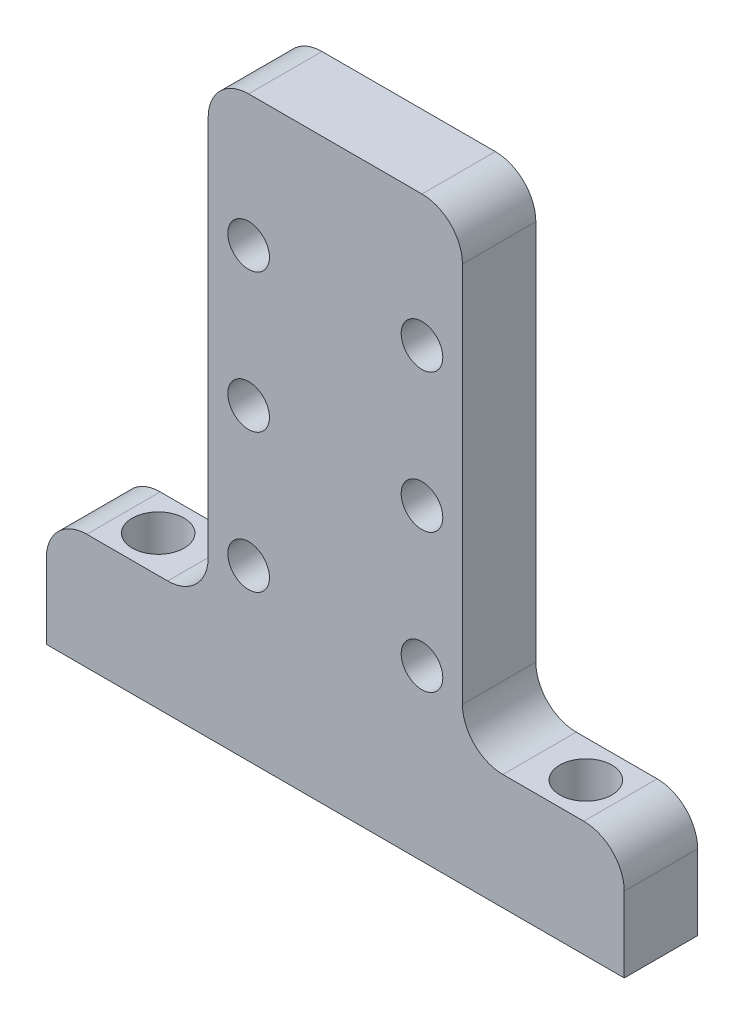
SolidWorks part; units mm, degrees
ref_plane "Front Plane" through (0, 0, 0) normal (0, 0, 1) x (1, 0, 0)
ref_plane "Top Plane" through (0, 0, 0) normal (0, 1, 0) x (1, 0, 0)
ref_plane "Right Plane" through (0, 0, 0) normal (1, 0, 0) x (0, 0, -1)
sketch "Sketch1" plane through (0, 0, 0) normal (0, 0, 1) x (1, 0, 0)
  line L0 (-25, 0) -> (25, 0)
  line L1 (25, 0) -> (25, 10)
  line L2 (25, 10) -> (11, 10)
  line L3 (11, 10) -> (11, 50)
  line L4 (11, 50) -> (-11, 50)
  line L5 (0, 50) -> (0, 0) construction
  line L6 (-25, 0) -> (-25, 10)
  line L7 (-25, 10) -> (-11, 10)
  line L8 (-11, 10) -> (-11, 50)
  dimension "D1" = 50
  dimension "D2" = 22
  dimension "D3" = 40
  dimension "D4" = 10
extrude "Boss-Extrude1" add sketch "Sketch1" along normal blind 6.35
sketch "Sketch4" plane through (0, 10, 0) normal (0, 1, 0) x (1, 0, 0)
  line L0 (-25, -3.175) -> (25, -3.175) construction
  line L1 (-25, -6.35) -> (-25, 0) construction
  line L2 (25, -6.35) -> (25, 0) construction
  line L3 (0, 0) -> (0, -6.35) construction
  line L4 (-11, 0) -> (-25, 0) construction
  line L5 (-11, -6.35) -> (-25, -6.35) construction
  point P12 (0, -3.175)
  point P13 (-18.5, -3.175)
  point P14 (18.5, -3.175)
  dimension "D1" = 37
hole_wizard "M4 Clearance Hole1" positions "Sketch8" profile "Sketch7" hole size "M4" standard "ANSI Metric" end condition through all
sketch "Sketch8" plane through (0, 10, 0) normal (0, 1, 0) x (1, 0, 0)
  point P0 (-18.5, -3.175)
  point P3 (18.5, -3.175)
sketch "Sketch7" plane through (-18.5, 10, 3.175) normal (1, 0, 0) x (0, 0, 1)
  line L0 (0, 0) -> (0, 10)
  line L1 (0, 10) -> (2.25, 10)
  line L2 (2.25, 10) -> (2.25, 0)
  line L5 (2.25, 0) -> (0, 0)
  line L11 (0, -6.35) -> (0, 107.95) construction
  dimension "Thru Hole Dia." = 4.5
  dimension "Thru Hole Depth" = 10
sketch "Sketch9" plane through (0, 0, 6.35) normal (0, 0, 1) x (1, 0, 0)
  line L0 (0, 50) -> (0, 0) construction
  line L1 (11, 50) -> (-11, 50) construction
  line L2 (-25, 0) -> (25, 0) construction
  line L3 (7.5, 50) -> (7.5, 0) construction
  line L4 (-7.5, 50) -> (-7.5, 0) construction
  line L5 (-7.5, 26.65) -> (-7.5, 14.65) construction
  line L6 (7.5, 38.65) -> (7.5, 26.65) construction
  point P6 (-7.5, 26.65)
  point P7 (-7.5, 14.65)
  point P8 (7.5, 26.65)
  point P9 (7.5, 38.65)
  point P18 (-7.5, 38.65)
  point P19 (7.5, 14.65)
  dimension "D1" = 15
  dimension "D2" = 12
  dimension "D3" = 26.65
hole_wizard "M3 Clearance Hole2" positions "Sketch11" profile "Sketch10" hole size "M3" standard "ANSI Metric" end condition through all
sketch "Sketch11" plane through (0, 0, 6.35) normal (0, 0, 1) x (1, 0, 0)
  point P0 (-7.5, 26.65)
  point P3 (7.5, 38.65)
  point P6 (-7.5, 14.65)
  point P9 (7.5, 26.65)
  point P12 (-7.5, 38.65)
  point P15 (7.5, 14.65)
sketch "Sketch10" plane through (-7.5, 26.65, 6.35) normal (1, 0, 0) x (0, -1, 0)
  line L0 (0, 0) -> (0, 6.35)
  line L1 (0, 6.35) -> (1.8, 6.35)
  line L2 (1.8, 6.35) -> (1.8, 0)
  line L5 (1.8, 0) -> (0, 0)
  line L11 (0, -6.35) -> (0, 107.95) construction
  dimension "Thru Hole Dia." = 3.6
  dimension "Thru Hole Depth" = 6.35
fillet "Fillet1" radius 3.5 2 edges at (11, 10, 3.175) (-11, 10, 3.175)
fillet "Fillet2" radius 3.5 4 edges at (-25, 10, 3.175) (25, 10, 3.175) (11, 50, 3.175) (-11, 50, 3.175)
equation "\"D1\"=7.5"
